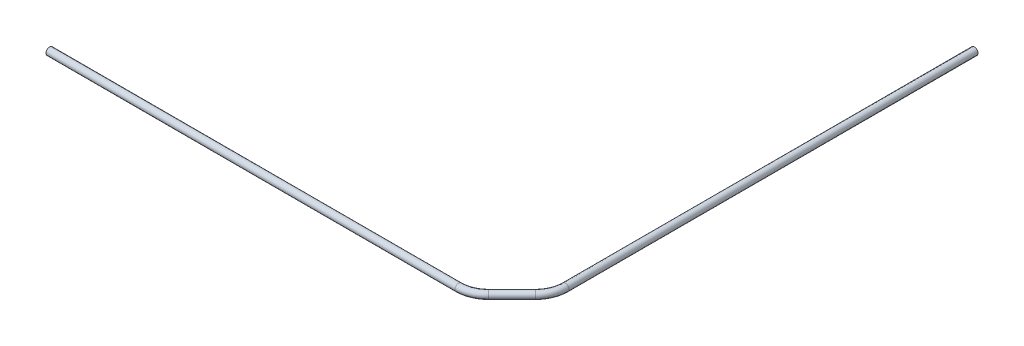
SolidWorks part; units mm, degrees
material "AISI 1020"
ref_plane "Спереди" through (0, 0, 0) normal (0, 0, 1) x (1, 0, 0)
ref_plane "Сверху" through (0, 0, 0) normal (0, 1, 0) x (1, 0, 0)
ref_plane "Справа" through (0, 0, 0) normal (1, 0, 0) x (0, 0, -1)
sketch "Эскиз1" plane through (0, 0, 0) normal (0, 1, 0) x (1, 0, 0)
  line L0 (18, 750) -> (18, 70.7107)
  line L1 (3.3553, 35.3553) -> (-35.3553, -3.3553)
  line L2 (-70.7107, -18) -> (-750, -18)
  line L3 (6, 500) -> (6, 1000) construction
  line L4 (-1000, -6) -> (-500, -6) construction
  arc A0 (-35.3553, -3.3553) -> (-70.7107, -18) centre (-70.7107, 32) cw
  arc A1 (18, 70.7107) -> (3.3553, 35.3553) centre (-32, 70.7107) cw
  point P16 (18, 50)
  dimension "D6" = 50
  dimension "D1" = 250
  dimension "D2" = 250
  dimension "D3" = 12
  dimension "D4" = 12
  dimension "D5" = 50
ref_plane "Плоскость1" through (-750, -400, -12) normal (-1, 0, 0) x (0, 0, 1)
sketch "Эскиз2" plane through (-750, -400, -12) normal (-1, 0, 0) x (0, 0, 1)
  circle A0 centre (30, 400) radius 6
  dimension "D1" = 12
sweep "По траектории1" add profiles "Эскиз2" path "Эскиз1"
